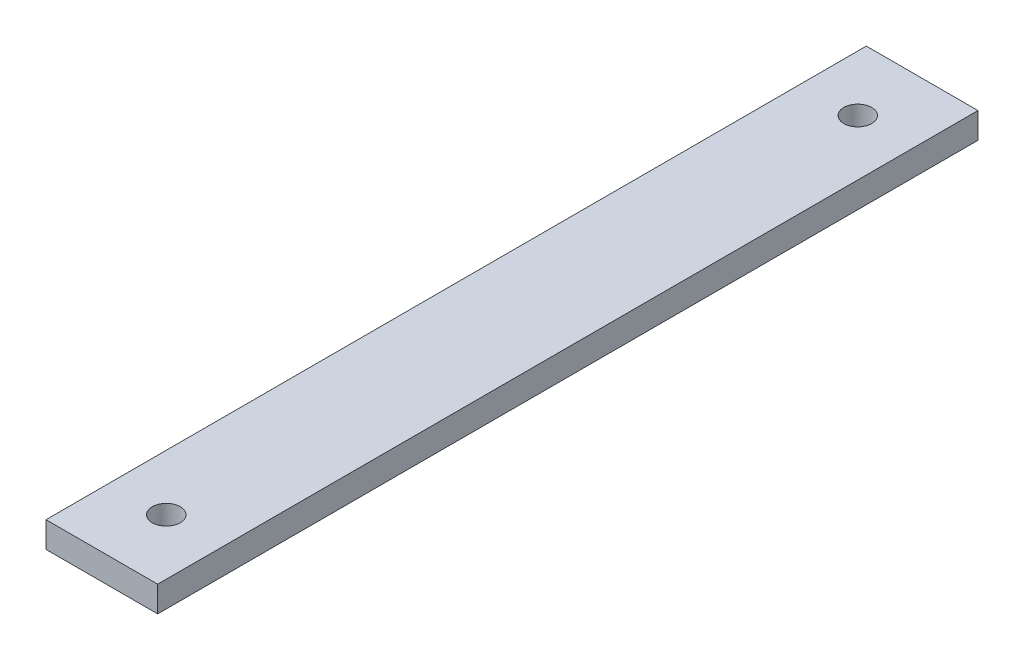
SolidWorks part; units mm, degrees
ref_plane "Front Plane" through (0, 0, 0) normal (0, 0, 1) x (1, 0, 0)
ref_plane "Top Plane" through (0, 0, 0) normal (0, 1, 0) x (1, 0, 0)
ref_plane "Right Plane" through (0, 0, 0) normal (1, 0, 0) x (0, 0, -1)
sketch "Sketch1" plane through (0, 0, 0) normal (0, 1, 0) x (1, 0, 0)
  line L1 (-76.2365, 44.4549) -> (-50.2365, 44.4549)
  line L2 (-76.2365, 44.4549) -> (-76.2365, -146.5451)
  line L3 (-76.2365, -146.5451) -> (-50.2365, -146.5451)
  line L4 (-50.2365, 44.4549) -> (-50.2365, -146.5451)
  dimension "D1" = 191
  dimension "D2" = 26
extrude "Boss-Extrude1" add sketch "Sketch1" along normal blind 6
sketch "Sketch2" plane through (0, 0, 0) normal (0, -1, 0) x (-1, 0, 0)
  line L0 (63.2365, -146.5451) -> (63.2365, -131.5451) construction
  line L1 (76.2365, -146.5451) -> (50.2365, -146.5451) construction
  line L2 (63.2365, 44.4549) -> (63.2365, 29.4549) construction
  line L3 (50.2365, 44.4549) -> (76.2365, 44.4549) construction
  circle A0 centre (63.2365, -131.5451) radius 3.25
  circle A1 centre (63.2365, 29.4549) radius 3.25
  point P10 (63.2365, -130.693)
extrude "Cut-Extrude1" cut sketch "Sketch2" against normal blind 10
